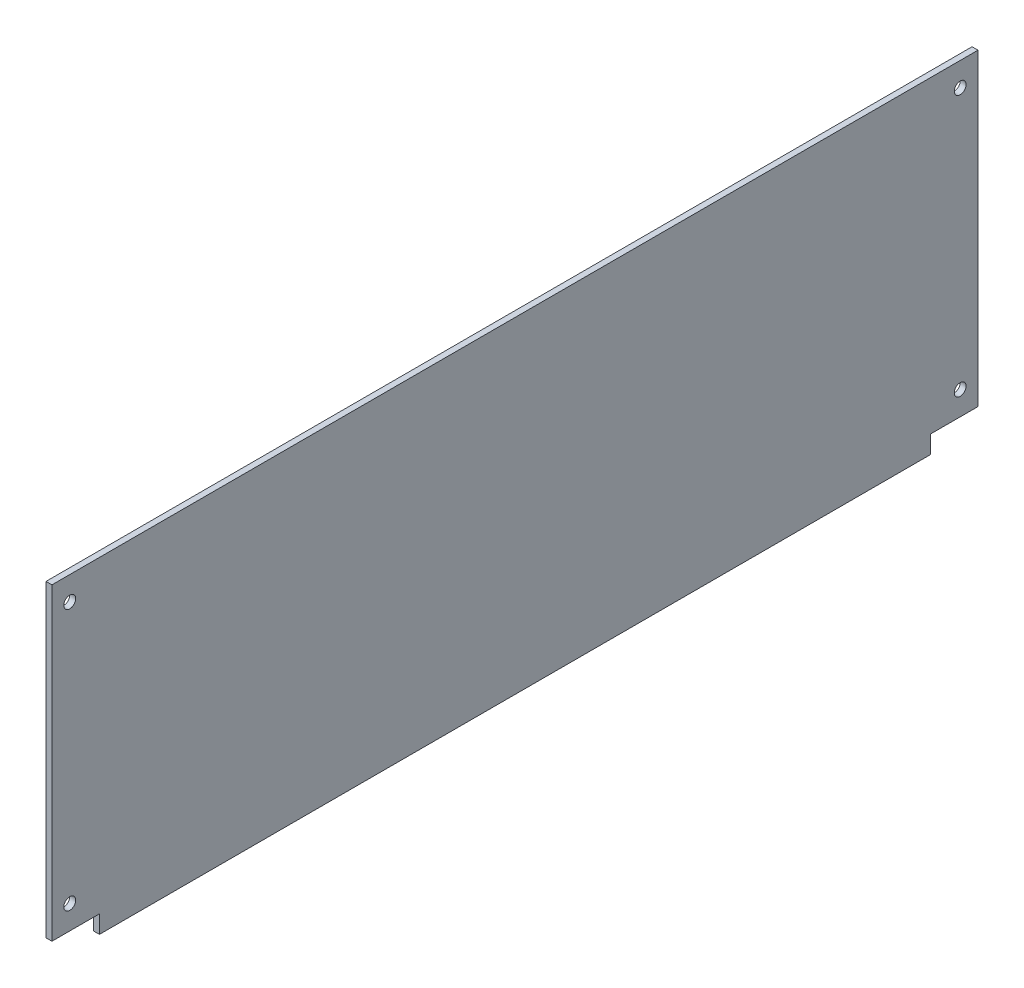
SolidWorks part; units mm, degrees
ref_plane "Front Plane" through (0, 0, 0) normal (0, 0, 1) x (1, 0, 0)
ref_plane "Top Plane" through (0, 0, 0) normal (0, 1, 0) x (1, 0, 0)
ref_plane "Right Plane" through (0, 0, 0) normal (1, 0, 0) x (0, 0, -1)
sketch "Sketch1" plane through (0, 0, 0) normal (0, 0, 1) x (1, 0, 0)
  line L6 (0, 0) -> (0, 275)
  line L7 (5, 0) -> (5, 275)
  line L8 (5, 275) -> (0, 275)
  line L9 (5, 0) -> (0, 0)
  dimension "D1" = 5
  dimension "D2" = 275
extrude "Boss-Extrude1" add sketch "Sketch1" along normal blind 700
ref_plane "Plane1" through (0, 15, 0) normal (0, -1, 0) x (-1, 0, 0)
ref_plane "Plane2" through (0, 0, 350) normal (0, 0, -1) x (-1, 0, 0)
sketch "Sketch2" plane through (0, 15, 0) normal (0, -1, 0) x (-1, 0, 0)
  line L0 (-5, 0) -> (-5, 40)
  line L1 (-5, 40) -> (0, 40)
  line L2 (0, 40) -> (0, 0)
  line L3 (0, 0) -> (-5, 0)
  dimension "D1" = 40
extrude "Boss-Extrude2" add sketch "Sketch2" against normal blind 260
mirror "Mirror1" about plane through (0, 0, 350) normal (0, 0, -1) of "Boss-Extrude2"
sketch "Sketch3" plane through (0, 0, 0) normal (-1, 0, 0) x (0, 0, 1)
  line L0 (-25, 40) -> (-25, 30) construction
  line L1 (-25, 260) -> (-25, 250) construction
  circle A0 centre (-25, 255) radius 5
  circle A1 centre (-25, 35) radius 5
  point P3 (-25, 255)
  point P4 (-25, 35)
  dimension "D4" = 10
  dimension "D5" = 10
extrude "Cut-Extrude1" cut sketch "Sketch3" against normal through all
ref_plane "Plane3" through (0, 0, 350) normal (0, 0, -1) x (-1, 0, 0)
mirror "Mirror2" about plane through (0, 0, 350) normal (0, 0, -1) of "Cut-Extrude1"
